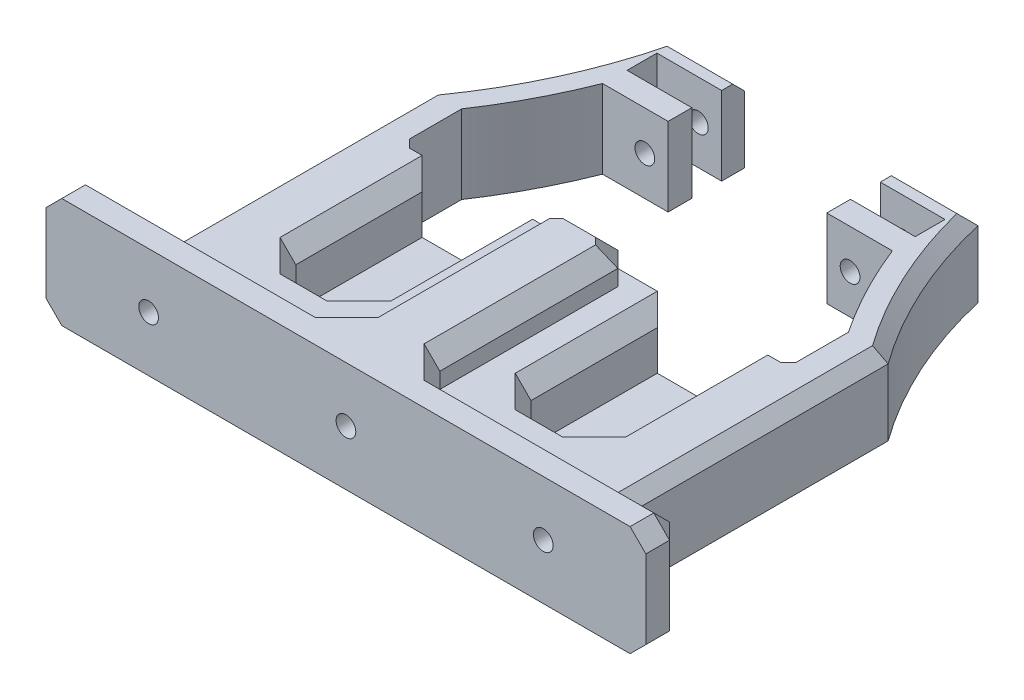
SolidWorks part; units mm, degrees
ref_plane "Front Plane" through (0, 0, 0) normal (0, 0, 1) x (1, 0, 0)
ref_plane "Top Plane" through (0, 0, 0) normal (0, 1, 0) x (1, 0, 0)
ref_plane "Right Plane" through (0, 0, 0) normal (1, 0, 0) x (0, 0, -1)
sketch "Sketch1" plane through (0, 0, 0) normal (0, 1, 0) x (1, 0, 0)
  line L0 (0, -35) -> (0, 35) construction
  line L1 (-43, 35) -> (-43, -35) construction
  line L2 (43, 35) -> (43, -35) construction
  line L3 (-43, -35) -> (43, -35) construction
  line L4 (-19.6142, -12) -> (19.6142, -12) construction
  line L5 (-10.05, -13) -> (-19.529, -13)
  line L8 (18.3602, -22.68) -> (10.05, -22.68)
  line L9 (-10.05, -13) -> (-10.05, -15.9)
  line L10 (10.05, -13) -> (10.05, -15.9)
  line L11 (-10.05, -22.68) -> (-18.3602, -22.68)
  line L14 (10.05, -13) -> (19.529, -13)
  line L15 (-10.05, -19.68) -> (-10.05, -22.68)
  line L16 (10.05, -19.68) -> (10.05, -22.68)
  line L17 (-29, -45) -> (29, -45)
  line L20 (-24.5, -42) -> (24.5, -42)
  line L21 (-29, -45) -> (-29, -33.854)
  line L22 (29, -33.854) -> (29, -45)
  line L23 (24.5, -42) -> (24.5, -34.3891)
  line L24 (-24.5, -34.3891) -> (-24.5, -42)
  line L31 (-18.25, -15.9) -> (-18.25, -19.68)
  line L32 (-10.05, -19.68) -> (-18.25, -19.68)
  line L33 (-10.05, -15.9) -> (-18.25, -15.9)
  line L34 (10.05, -19.68) -> (18.25, -19.68)
  line L35 (18.25, -15.9) -> (18.25, -19.68)
  line L36 (10.05, -15.9) -> (18.25, -15.9)
  arc A0 (-43, -35) -> (-43, 35) centre (-75.8481, 0) ccw construction
  arc A1 (43, -35) -> (43, 35) centre (75.8481, 0) cw construction
  arc A2 (-29, -33.854) -> (-19.529, -13) centre (-75.8481, 0) ccw
  arc A3 (29, -33.854) -> (19.529, -13) centre (75.8481, 0) cw
  arc A4 (-24.5, -34.3891) -> (-18.3602, -22.68) centre (-75.8481, 0) ccw
  arc A5 (24.5, -34.3891) -> (18.3602, -22.68) centre (75.8481, 0) cw
  arc A9 (-33.5562, -45.0625) -> (-33.5562, 45.0625) centre (-75.8481, 0) ccw construction
  arc A11 (36.2935, -42.1458) -> (36.2935, 42.1458) centre (75.8481, 0) cw construction
  arc A12 (-36.2935, -42.1458) -> (-36.2935, 42.1458) centre (-75.8481, 0) ccw construction
  point P4 (0, 0)
  point P7 (-43, 0)
  dimension "D2" = 48
  dimension "D1" = 70
  dimension "D3" = 43
  dimension "D4" = 8.2
  dimension "D5" = 9.8
  dimension "D7" = 23
  dimension "D8" = 3.78
  dimension "D9" = 2
  dimension "D10" = 2.9
  dimension "D13" = 10.05
  dimension "D15" = 29
  dimension "D16" = 29
  dimension "D17" = 24.5
  dimension "D18" = 24.5
  dimension "D19" = 3
  dimension "D20" = 7
  dimension "D21" = 3
  dimension "D6" = 9.8
  dimension "D14" = 4
extrude "Boss-Extrude1" add sketch "Sketch1" along normal blind 9.95
sketch "Sketch2" plane through (0, 0, 45) normal (0, 0, 1) x (1, 0, 0)
  line L4 (-29, 0) -> (29, 0)
  line L5 (29, 0) -> (29, 9.95)
  line L6 (29, 9.95) -> (-29, 9.95)
  line L7 (-29, 9.95) -> (-29, 0)
  line L8 (-29, 0) -> (29, 0)
  line L9 (29, 0) -> (29, 9.95)
  line L10 (29, 9.95) -> (-29, 9.95)
  line L11 (-29, 9.95) -> (-29, 0)
  dimension "D1" = 0
extrude "Boss-Extrude2" add sketch "Sketch2" along normal blind 8.55
sketch "Sketch3" plane through (0, 9.95, 0) normal (0, 1, 0) x (1, 0, 0)
  line L1 (-4.9, -53.55) -> (4.9, -53.55)
  line L2 (-4.9, -53.55) -> (-4.9, -42)
  line L3 (-4.9, -42) -> (4.9, -42)
  line L4 (4.9, -53.55) -> (4.9, -42)
  line L5 (-4.9, -53.55) -> (4.9, -42) construction
  line L6 (-4.9, -42) -> (4.9, -53.55) construction
  line L18 (-10.05, -19.68) -> (-18.25, -19.68)
  line L19 (-10.05, -19.68) -> (-18.25, -19.68)
  line L20 (-10.05, -15.9) -> (-10.05, -13)
  line L21 (-10.05, -13) -> (-19.529, -13)
  line L22 (-29, -33.854) -> (-29, -53.55)
  line L23 (-29, -53.55) -> (29, -53.55)
  line L24 (29, -53.55) -> (29, -33.854)
  line L25 (19.529, -13) -> (10.05, -13)
  line L26 (10.05, -13) -> (10.05, -15.9)
  line L27 (-18.25, -19.68) -> (-18.25, -15.9)
  line L28 (-18.25, -19.68) -> (-18.25, -15.9)
  line L29 (10.05, -19.68) -> (10.05, -22.68)
  line L30 (10.05, -22.68) -> (18.3602, -22.68)
  line L31 (24.5, -34.3891) -> (24.5, -42)
  line L32 (24.5, -42) -> (-24.5, -42)
  line L33 (-24.5, -42) -> (-24.5, -34.3891)
  line L34 (-18.3602, -22.68) -> (-10.05, -22.68)
  line L35 (-10.05, -22.68) -> (-10.05, -19.68)
  line L38 (-10.05, -15.9) -> (-10.05, -13)
  line L39 (-10.05, -13) -> (-19.529, -13)
  line L40 (-29, -33.854) -> (-29, -53.55)
  line L41 (-29, -53.55) -> (29, -53.55)
  line L42 (29, -53.55) -> (29, -33.854)
  line L43 (19.529, -13) -> (10.05, -13)
  line L44 (10.05, -13) -> (10.05, -15.9)
  line L47 (10.05, -19.68) -> (10.05, -22.68)
  line L48 (10.05, -22.68) -> (18.3602, -22.68)
  line L49 (24.5, -34.3891) -> (24.5, -42)
  line L50 (24.5, -42) -> (-24.5, -42)
  line L51 (-24.5, -42) -> (-24.5, -34.3891)
  line L52 (-18.3602, -22.68) -> (-10.05, -22.68)
  line L53 (-10.05, -22.68) -> (-10.05, -19.68)
  line L62 (-18.25, -15.9) -> (-10.05, -15.9)
  line L64 (-18.25, -15.9) -> (-10.05, -15.9)
  line L66 (10.05, -15.9) -> (18.25, -15.9)
  line L67 (10.05, -15.9) -> (18.25, -15.9)
  line L68 (18.25, -15.9) -> (18.25, -19.68)
  line L69 (18.25, -15.9) -> (18.25, -19.68)
  line L70 (18.25, -19.68) -> (10.05, -19.68)
  line L71 (18.25, -19.68) -> (10.05, -19.68)
  arc A7 (-29, -33.854) -> (-19.529, -13) centre (-75.8481, 0) ccw
  arc A8 (19.529, -13) -> (29, -33.854) centre (75.8481, 0) ccw
  arc A10 (18.3602, -22.68) -> (24.5, -34.3891) centre (75.8481, 0) ccw
  arc A11 (-24.5, -34.3891) -> (-18.3602, -22.68) centre (-75.8481, 0) ccw
  arc A13 (-29, -33.854) -> (-19.529, -13) centre (-75.8481, 0) ccw
  arc A14 (19.529, -13) -> (29, -33.854) centre (75.8481, 0) ccw
  arc A16 (18.3602, -22.68) -> (24.5, -34.3891) centre (75.8481, 0) ccw
  arc A17 (-24.5, -34.3891) -> (-18.3602, -22.68) centre (-75.8481, 0) ccw
  point P2 (0, -47.775)
  line M36 (-29, -53.55) -> (29, -53.55)
  line M48 (24.5, -42) -> (-24.5, -42)
  dimension "D2" = 9.8
  dimension "D1" = 0
extrude "Boss-Extrude3" add sketch "Sketch3" along normal blind 4 contours L4 L2 M36 M48
sketch "Sketch4" plane through (0, 0, 53.55) normal (0, 0, 1) x (1, 0, 0)
  line L8 (-29, 9.95) -> (-29, 0)
  line L9 (-29, 0) -> (29, 0)
  line L10 (29, 0) -> (29, 9.95)
  line L11 (29, 9.95) -> (4.9, 9.95)
  line L12 (4.9, 9.95) -> (4.9, 13.95)
  line L13 (4.9, 13.95) -> (-4.9, 13.95)
  line L14 (-4.9, 13.95) -> (-4.9, 9.95)
  line L15 (-4.9, 9.95) -> (-29, 9.95)
  line L16 (-29, 9.95) -> (-29, 0)
  line L17 (-29, 0) -> (29, 0)
  line L18 (29, 0) -> (29, 9.95)
  line L19 (29, 9.95) -> (4.9, 9.95)
  line L20 (4.9, 9.95) -> (4.9, 13.95)
  line L21 (4.9, 13.95) -> (-4.9, 13.95)
  line L22 (-4.9, 13.95) -> (-4.9, 9.95)
  line L23 (-4.9, 9.95) -> (-29, 9.95)
  dimension "D1" = 0
extrude "Boss-Extrude4" add sketch "Sketch4" along normal blind 20
chamfer "Chamfer1" distance 2 angle 45 2 edges at (-4.9, 11.95, 42) (4.9, 11.95, 42)
sketch "Sketch5" plane through (0, 0, 13) normal (0, 0, -1) x (-1, 0, 0)
  line L0 (10.05, 0) -> (19.529, 0) construction
  line L1 (19.529, 0) -> (19.529, 9.95) construction
  line L2 (19.529, 9.95) -> (10.05, 9.95) construction
  line L3 (10.05, 9.95) -> (10.05, 0) construction
  line L4 (-19.529, 0) -> (-10.05, 0) construction
  line L5 (-10.05, 0) -> (-10.05, 9.95) construction
  line L6 (-10.05, 9.95) -> (-19.529, 9.95) construction
  line L7 (-19.529, 9.95) -> (-19.529, 0) construction
  line L8 (10.05, 0) -> (19.529, 0)
  line L9 (19.529, 0) -> (19.529, 9.95)
  line L10 (19.529, 9.95) -> (10.05, 9.95)
  line L11 (10.05, 9.95) -> (10.05, 0)
  line L12 (-19.529, 0) -> (-10.05, 0)
  line L13 (-10.05, 0) -> (-10.05, 9.95)
  line L14 (-10.05, 9.95) -> (-19.529, 9.95)
  line L15 (-19.529, 9.95) -> (-19.529, 0)
  line L16 (-19.529, 4.975) -> (19.529, 4.975) construction
  circle A0 centre (-13, 4.975) radius 1.25
  circle A1 centre (13, 4.975) radius 1.25
  point P14 (0, 4.975)
  dimension "D3" = 2.5
  dimension "D1" = 13
  dimension "D2" = 26
extrude "Cut-Extrude1" cut sketch "Sketch5" against normal up to surface (9.68 mm away) contours L16 A0 | A0 L16 | A1 L16 | L16 A1 up to face at (14.2051, 4.975, 22.68)
chamfer "Chamfer2" distance 1 angle 45 2 edges at (-14.25, 4.975, 13) (11.75, 4.975, 13)
sketch "Sketch6" plane through (0, 0, 73.55) normal (0, 0, 1) x (1, 0, 0)
  line L0 (4.9, 13.95) -> (-4.9, 13.95) construction
  line L1 (-38, 0) -> (38, 0)
  line L2 (-38, 0) -> (-38, 13.95)
  line L3 (-38, 13.95) -> (38, 13.95)
  line L4 (38, 0) -> (38, 13.95)
  line L5 (-38, 0) -> (38, 13.95) construction
  line L6 (-38, 13.95) -> (38, 0) construction
  line L7 (-29, 0) -> (29, 0) construction
  line L8 (29, 0) -> (29, 9.95) construction
  line L9 (29, 9.95) -> (4.9, 9.95) construction
  line L10 (4.9, 9.95) -> (4.9, 13.95) construction
  line L11 (-29, 9.95) -> (-29, 0) construction
  line L12 (-4.9, 13.95) -> (-4.9, 9.95) construction
  line L13 (-4.9, 9.95) -> (-29, 9.95) construction
  line L14 (29, 0) -> (29, 9.95)
  line L15 (29, 9.95) -> (4.9, 9.95)
  line L16 (4.9, 9.95) -> (4.9, 13.95)
  line L17 (-29, 9.95) -> (-29, 0)
  line L18 (-4.9, 13.95) -> (-4.9, 9.95)
  line L19 (-4.9, 9.95) -> (-29, 9.95)
  point P0 (0, 6.975)
  line M5 (-4.9, 9.95) -> (-29, 9.95)
  line M6 (-29, 9.95) -> (-29, 0)
  line M8 (29, 0) -> (29, 9.95)
  line M9 (29, 9.95) -> (4.9, 9.95)
  line M10 (4.9, 9.95) -> (4.9, 13.95)
  line M12 (-4.9, 13.95) -> (-4.9, 9.95)
  dimension "D2" = 76
extrude "Boss-Extrude5" add sketch "Sketch6" against normal blind 5 contours L1 L4 L3 M10 M9 M8 | L3 L2 L1 M6 M5 M12
chamfer "Chamfer3" distance 2 angle 45 17 edges at (-33.5, 0, 68.55) (33.5, 0, 68.55) (-38, 0, 71.05) (-38, 6.975, 68.55) (38, 0, 71.05) (38, 6.975, 68.55) (-38, 13.95, 71.05) (38, 13.95, 71.05) (-4.9, 11.95, 68.55) (4.9, 11.95, 68.55) (21.45, 13.95, 68.55) (-21.45, 13.95, 68.55) (-4.9, 13.95, 56.275) (-3.9, 13.95, 43) (0, 13.95, 42) (3.9, 13.95, 43) (4.9, 13.95, 56.275)
sketch "Sketch7" plane through (0, 9.95, 0) normal (0, 1, 0) x (1, 0, 0)
  line L1 (-19.9, -42) -> (-9.9, -42)
  line L2 (-19.9, -42) -> (-19.9, -62)
  line L3 (-19.9, -62) -> (-9.9, -62)
  line L4 (-9.9, -42) -> (-9.9, -62)
  line L5 (9.9, -42) -> (19.9, -42)
  line L6 (9.9, -42) -> (9.9, -62)
  line L7 (9.9, -62) -> (19.9, -62)
  line L8 (19.9, -42) -> (19.9, -62)
  line L14 (-29, -68.55) -> (-6.9, -68.55)
  line L15 (-6.9, -68.55) -> (-4.9, -66.55)
  line L16 (-4.9, -66.55) -> (-4.9, -44)
  line L17 (-4.9, -44) -> (-2.9, -42)
  line L18 (-2.9, -42) -> (-24.5, -42)
  line L19 (-24.5, -42) -> (-24.5, -34.3891)
  line L20 (-18.3602, -22.68) -> (-10.05, -22.68)
  line L21 (-10.05, -22.68) -> (-10.05, -19.68)
  line L22 (-10.05, -19.68) -> (-18.25, -19.68)
  line L23 (-10.05, -19.68) -> (-18.25, -19.68)
  line L24 (-18.25, -19.68) -> (-18.25, -15.9)
  line L25 (-10.05, -15.9) -> (-10.05, -13)
  line L26 (-10.05, -13) -> (-19.529, -13)
  line L27 (-29, -33.854) -> (-29, -68.55)
  line L28 (-29, -68.55) -> (-6.9, -68.55)
  line L29 (-6.9, -68.55) -> (-4.9, -66.55)
  line L30 (-4.9, -66.55) -> (-4.9, -44)
  line L31 (-4.9, -44) -> (-2.9, -42)
  line L32 (-2.9, -42) -> (-24.5, -42)
  line L33 (-24.5, -42) -> (-24.5, -34.3891)
  line L34 (-18.3602, -22.68) -> (-10.05, -22.68)
  line L35 (-10.05, -22.68) -> (-10.05, -19.68)
  line L39 (-10.05, -15.9) -> (-10.05, -13)
  line L40 (-10.05, -13) -> (-19.529, -13)
  line L41 (-29, -33.854) -> (-29, -68.55)
  line L46 (4.9, -44) -> (4.9, -66.55)
  line L47 (4.9, -66.55) -> (6.9, -68.55)
  line L48 (6.9, -68.55) -> (29, -68.55)
  line L49 (29, -68.55) -> (29, -33.854)
  line L50 (19.529, -13) -> (10.05, -13)
  line L51 (10.05, -13) -> (10.05, -15.9)
  line L52 (10.05, -15.9) -> (18.25, -15.9)
  line L53 (10.05, -15.9) -> (18.25, -15.9)
  line L54 (18.25, -15.9) -> (18.25, -19.68)
  line L55 (10.05, -19.68) -> (10.05, -22.68)
  line L56 (10.05, -22.68) -> (18.3602, -22.68)
  line L57 (24.5, -34.3891) -> (24.5, -42)
  line L58 (24.5, -42) -> (2.9, -42)
  line L59 (2.9, -42) -> (4.9, -44)
  line L60 (4.9, -44) -> (4.9, -66.55)
  line L61 (4.9, -66.55) -> (6.9, -68.55)
  line L62 (6.9, -68.55) -> (29, -68.55)
  line L63 (29, -68.55) -> (29, -33.854)
  line L64 (19.529, -13) -> (10.05, -13)
  line L65 (10.05, -13) -> (10.05, -15.9)
  line L69 (10.05, -19.68) -> (10.05, -22.68)
  line L70 (10.05, -22.68) -> (18.3602, -22.68)
  line L71 (24.5, -34.3891) -> (24.5, -42)
  line L72 (24.5, -42) -> (2.9, -42)
  line L73 (2.9, -42) -> (4.9, -44)
  line L78 (-18.25, -19.68) -> (-18.25, -15.9)
  line L79 (-18.25, -15.9) -> (-10.05, -15.9)
  line L80 (-18.25, -15.9) -> (-10.05, -15.9)
  line L81 (18.25, -15.9) -> (18.25, -19.68)
  line L82 (18.25, -19.68) -> (10.05, -19.68)
  line L83 (18.25, -19.68) -> (10.05, -19.68)
  arc A2 (-24.5, -34.3891) -> (-18.3602, -22.68) centre (-75.8481, 0) ccw
  arc A3 (-29, -33.854) -> (-19.529, -13) centre (-75.8481, 0) ccw
  arc A4 (-24.5, -34.3891) -> (-18.3602, -22.68) centre (-75.8481, 0) ccw
  arc A5 (-29, -33.854) -> (-19.529, -13) centre (-75.8481, 0) ccw
  arc A6 (19.529, -13) -> (29, -33.854) centre (75.8481, 0) ccw
  arc A7 (18.3602, -22.68) -> (24.5, -34.3891) centre (75.8481, 0) ccw
  arc A8 (19.529, -13) -> (29, -33.854) centre (75.8481, 0) ccw
  arc A9 (18.3602, -22.68) -> (24.5, -34.3891) centre (75.8481, 0) ccw
  line M45 (-2.9, -42) -> (-24.5, -42)
  dimension "D3" = 10
  dimension "D4" = 5
  dimension "D5" = 20
  dimension "D6" = 5
  dimension "D7" = 10
  dimension "D8" = 20
  dimension "D1" = 0
  dimension "D2" = 0
extrude "Cut-Extrude2" cut sketch "Sketch7" against normal blind 7 contours L4 L2 L3 M45 | L8 L5 L6 L7
chamfer "Chamfer4" distance 2 angle 45 14 edges at (9.9, 6.45, 42) (-9.9, 6.45, 42) (-9.9, 9.95, 52) (-9.9, 6.45, 62) (-14.9, 9.95, 62) (-19.9, 6.45, 42) (-19.9, 6.45, 62) (-19.9, 9.95, 52) (9.9, 9.95, 52) (14.9, 9.95, 62) (19.9, 6.45, 42) (19.9, 9.95, 52) (19.9, 6.45, 62) (9.9, 6.45, 62)
sketch "Sketch8" plane through (0, 0, 73.55) normal (0, 0, 1) x (1, 0, 0)
  line L0 (-38, 6.975) -> (38, 6.975) construction
  line L1 (0, 13.95) -> (0, 0) construction
  line L8 (-38, 11.95) -> (-38, 2)
  line L9 (-38, 2) -> (-36, 0)
  line L10 (-36, 0) -> (36, 0)
  line L11 (36, 0) -> (38, 2)
  line L12 (38, 2) -> (38, 11.95)
  line L13 (38, 11.95) -> (36, 13.95)
  line L14 (36, 13.95) -> (-36, 13.95)
  line L15 (-36, 13.95) -> (-38, 11.95)
  line L16 (-38, 11.95) -> (-38, 2)
  line L17 (-38, 2) -> (-36, 0)
  line L18 (-36, 0) -> (36, 0)
  line L19 (36, 0) -> (38, 2)
  line L20 (38, 2) -> (38, 11.95)
  line L21 (38, 11.95) -> (36, 13.95)
  line L22 (36, 13.95) -> (-36, 13.95)
  line L23 (-36, 13.95) -> (-38, 11.95)
  circle A0 centre (-25, 6.975) radius 1.25
  circle A1 centre (25, 6.975) radius 1.25
  circle A2 centre (0, 6.975) radius 1.25
  dimension "D2" = 2.5
  dimension "D3" = 25
  dimension "D1" = 0
chamfer "Chamfer5" distance 1 angle 45 2 edges at (-24.5, 4.975, 42) (24.5, 4.975, 42)
extrude "Cut-Extrude3" cut sketch "Sketch8" against normal blind 15 contours A0 | A1 | A2
chamfer "Chamfer6" distance 1.5 angle 45 6 edges at (29, 9.95, 51.202) (23.2212, 9.95, 23.9008) (14.7895, 9.95, 13) (-14.7895, 9.95, 13) (-23.2212, 9.95, 23.9008) (-29, 9.95, 51.202)
chamfer "Chamfer7" distance 2 angle 45 2 edges at (-14.9, 2.95, 42) (14.9, 2.95, 42)
